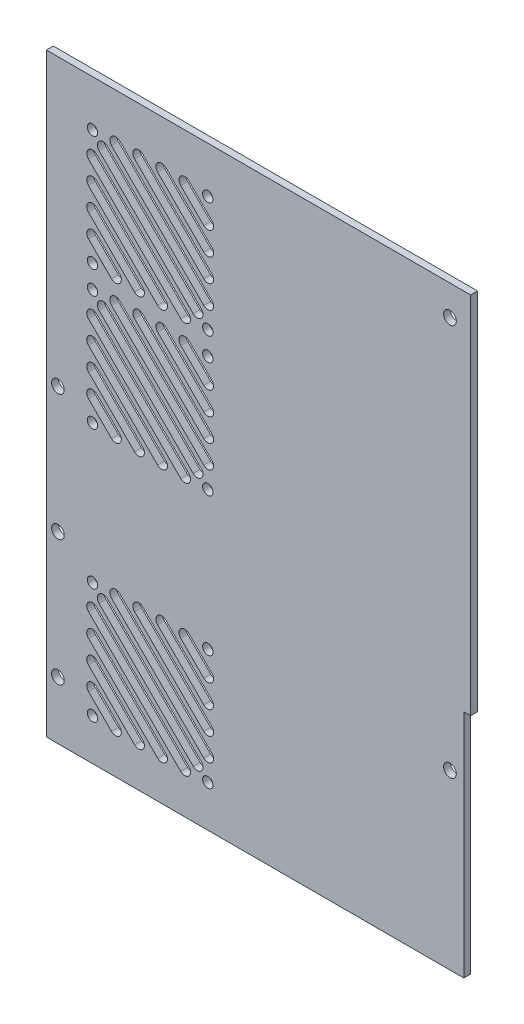
SolidWorks part; units mm, degrees
ref_plane "Front Plane" through (0, 0, 0) normal (0, 0, 1) x (1, 0, 0)
ref_plane "Top Plane" through (0, 0, 0) normal (0, 1, 0) x (1, 0, 0)
ref_plane "Right Plane" through (0, 0, 0) normal (1, 0, 0) x (0, 0, -1)
sketch "Sketch1" plane through (0, 0, 0) normal (0, 0, 1) x (1, 0, 0)
  line L1 (0, 0) -> (184, 0)
  line L2 (0, 0) -> (0, 258)
  line L3 (0, 258) -> (184, 258)
  line L4 (184, 0) -> (184, 258)
  dimension "D1" = 184
  dimension "D2" = 258
extrude "Boss-Extrude1" add sketch "Sketch1" along normal blind 3
sketch "Sketch2" plane through (0, 0, 0) normal (0, 0, -1) x (-1, 0, 0)
  line L0 (-175, 75) -> (-175, 245)
  circle A0 centre (-175, 75) radius 1.7 construction
  circle A1 centre (-5, 134.225) radius 2.2 construction
  circle A2 centre (-5, 79.6125) radius 2.2 construction
  circle A3 centre (-175, 75) radius 1.7
  circle A4 centre (-5, 134.225) radius 2.2
  circle A5 centre (-5, 79.6125) radius 2.2
  circle A6 centre (-5, 25) radius 2.15 construction
  circle A7 centre (-5, 25) radius 2.15
  point P0 (-175, 75)
  point P2 (-5, 134.225)
  point P4 (-5, 79.6125)
  point P11 (-175, 245)
  point P19 (-5, 25)
  dimension "D1" = 170
hole_wizard "M5 Clearance Hole1" positions "Sketch2" profile "Sketch3" hole size "M5" standard "ANSI Metric" end condition through all
sketch "Sketch3" plane through (175, 75, 0) normal (1, 0, 0) x (0, 1, 0)
  line L0 (0, 0) -> (0, 3)
  line L1 (0, 3) -> (2.75, 3)
  line L2 (2.75, 3) -> (2.75, 0)
  line L5 (2.75, 0) -> (0, 0)
  line L11 (0, -6.35) -> (0, 107.95) construction
  dimension "Thru Hole Dia." = 5.5
  dimension "Thru Hole Depth" = 3
sketch "Sketch4" plane through (0, 0, 0) normal (0, 0, -1) x (-1, 0, 0)
  line L1 (-70, 238) -> (-20, 238) construction
  line L2 (-70, 238) -> (-70, 188) construction
  line L3 (-70, 188) -> (-20, 188) construction
  line L4 (-20, 238) -> (-20, 188) construction
  line L5 (0, 258) -> (0, 0) construction
  line L6 (-184, 258) -> (0, 258) construction
  line L7 (-60, 238) -> (-70, 228) construction
  line L8 (-50, 238) -> (-70, 218) construction
  line L9 (-40, 238) -> (-70, 208) construction
  line L10 (-30, 238) -> (-70, 198) construction
  line L11 (-20, 238) -> (-70, 188) construction
  line L12 (-20, 228) -> (-60, 188) construction
  line L13 (-20, 218) -> (-50, 188) construction
  line L14 (-20, 208) -> (-40, 188) construction
  line L15 (-20, 198) -> (-30, 188) construction
  line L16 (-60, 238) -> (-70, 228) construction
  line L17 (-58.2322, 236.2322) -> (-68.2322, 226.2322)
  line L18 (-61.7678, 239.7678) -> (-71.7678, 229.7678)
  line L19 (-50, 238) -> (-70, 218) construction
  line L20 (-48.2322, 236.2322) -> (-68.2322, 216.2322)
  line L21 (-51.7678, 239.7678) -> (-71.7678, 219.7678)
  line L22 (-40, 238) -> (-70, 208) construction
  line L23 (-38.2322, 236.2322) -> (-68.2322, 206.2322)
  line L24 (-41.7678, 239.7678) -> (-71.7678, 209.7678)
  line L25 (-30, 238) -> (-70, 198) construction
  line L26 (-28.2322, 236.2322) -> (-68.2322, 196.2322)
  line L27 (-31.7678, 239.7678) -> (-71.7678, 199.7678)
  line L28 (-65.4038, 192.5962) -> (-24.5962, 233.4038) construction
  line L29 (-67.1716, 194.364) -> (-26.364, 235.1716)
  line L30 (-63.636, 190.8284) -> (-22.8284, 231.636)
  line L31 (-20, 228) -> (-60, 188) construction
  line L32 (-18.2322, 226.2322) -> (-58.2322, 186.2322)
  line L33 (-21.7678, 229.7678) -> (-61.7678, 189.7678)
  line L34 (-50, 188) -> (-20, 218) construction
  line L35 (-51.7678, 189.7678) -> (-21.7678, 219.7678)
  line L36 (-48.2322, 186.2322) -> (-18.2322, 216.2322)
  line L37 (-20, 208) -> (-40, 188) construction
  line L38 (-18.2322, 206.2322) -> (-38.2322, 186.2322)
  line L39 (-21.7678, 209.7678) -> (-41.7678, 189.7678)
  line L40 (-20, 198) -> (-30, 188) construction
  line L41 (-18.2322, 196.2322) -> (-28.2322, 186.2322)
  line L42 (-21.7678, 199.7678) -> (-31.7678, 189.7678)
  circle A0 centre (-70, 238) radius 4
  circle A1 centre (-20, 238) radius 4
  circle A2 centre (-70, 188) radius 4
  circle A3 centre (-20, 188) radius 3
  arc A4 (-58.2322, 236.2322) -> (-61.7678, 239.7678) centre (-60, 238) ccw
  arc A5 (-71.7678, 229.7678) -> (-68.2322, 226.2322) centre (-70, 228) ccw
  arc A6 (-48.2322, 236.2322) -> (-51.7678, 239.7678) centre (-50, 238) ccw
  arc A7 (-71.7678, 219.7678) -> (-68.2322, 216.2322) centre (-70, 218) ccw
  arc A8 (-38.2322, 236.2322) -> (-41.7678, 239.7678) centre (-40, 238) ccw
  arc A9 (-71.7678, 209.7678) -> (-68.2322, 206.2322) centre (-70, 208) ccw
  arc A10 (-28.2322, 236.2322) -> (-31.7678, 239.7678) centre (-30, 238) ccw
  arc A11 (-71.7678, 199.7678) -> (-68.2322, 196.2322) centre (-70, 198) ccw
  arc A12 (-67.1716, 194.364) -> (-63.636, 190.8284) centre (-65.4038, 192.5962) ccw
  arc A13 (-22.8284, 231.636) -> (-26.364, 235.1716) centre (-24.5962, 233.4038) ccw
  arc A14 (-18.2322, 226.2322) -> (-21.7678, 229.7678) centre (-20, 228) ccw
  arc A15 (-61.7678, 189.7678) -> (-58.2322, 186.2322) centre (-60, 188) ccw
  arc A16 (-51.7678, 189.7678) -> (-48.2322, 186.2322) centre (-50, 188) ccw
  arc A17 (-18.2322, 216.2322) -> (-21.7678, 219.7678) centre (-20, 218) ccw
  arc A18 (-18.2322, 206.2322) -> (-21.7678, 209.7678) centre (-20, 208) ccw
  arc A19 (-41.7678, 189.7678) -> (-38.2322, 186.2322) centre (-40, 188) ccw
  arc A20 (-18.2322, 196.2322) -> (-21.7678, 199.7678) centre (-20, 198) ccw
  arc A21 (-31.7678, 189.7678) -> (-28.2322, 186.2322) centre (-30, 188) ccw
  point P28 (-65, 233)
  point P33 (-60, 228)
  point P38 (-55, 223)
  point P43 (-50, 218)
  point P50 (-45, 213)
  point P55 (-40, 208)
  point P60 (-35, 203)
  point P65 (-30, 198)
  point P70 (-25, 193)
  dimension "D14" = 8
  dimension "D15" = 8
  dimension "D16" = 8
  dimension "D17" = 6
  dimension "D18" = 2.5
  dimension "D19" = 2.5
  dimension "D20" = 2.5
  dimension "D21" = 2.5
  dimension "D22" = 2.5
  dimension "D23" = 2.5
  dimension "D24" = 2.5
  dimension "D25" = 2.5
  dimension "D26" = 2.5
  dimension "D1" = 50
  dimension "D2" = 50
  dimension "D3" = 20
  dimension "D4" = 20
  dimension "D5" = 45
  dimension "D6" = 10
  dimension "D7" = 10
  dimension "D8" = 10
  dimension "D9" = 10
  dimension "D10" = 10
  dimension "D11" = 10
  dimension "D12" = 10
  dimension "D13" = 10
extrude "Cut-Extrude1" cut sketch "Sketch4" against normal blind 10 contours L18 A5 L17 A4 | L21 A7 L20 A6 | L24 A9 L23 A8 | L27 A11 L26 A10 | A13 L29 A12 L30 | L33 A15 L32 A14 | L36 A17 L35 A16 | L39 A19 L38 A18 | L42 A21 L41 A20
sketch "Sketch5" plane through (0, 0, 0) normal (0, 0, -1) x (-1, 0, 0)
  point P0 (-20, 188)
  point P2 (-70, 188)
  point P4 (-70, 238)
  point P6 (-20, 238)
hole_wizard "M4 Clearance Hole1" positions "Sketch5" profile "Sketch6" hole size "M4" standard "ANSI Metric" end condition through all
sketch "Sketch6" plane through (20, 188, 0) normal (1, 0, 0) x (0, 1, 0)
  line L0 (0, 0) -> (0, 3)
  line L1 (0, 3) -> (2.25, 3)
  line L2 (2.25, 3) -> (2.25, 0)
  line L5 (2.25, 0) -> (0, 0)
  line L11 (0, -6.35) -> (0, 107.95) construction
  dimension "Thru Hole Dia." = 4.5
  dimension "Thru Hole Depth" = 3
pattern_linear "LPattern1" count 2 spacing 60 along (0, -1, 0) of "Cut-Extrude1", "M4 Clearance Hole1"
pattern_linear "LPattern2" count 2 spacing 170 along (0, -1, 0) of "M4 Clearance Hole1", "Cut-Extrude1"
sketch "Sketch7" plane through (0, 0, 0) normal (0, 0, -1) x (-1, 0, 0)
  line L0 (0, 0) -> (-184, 0) construction
  line L1 (-184, 0) -> (-181, 0)
  line L2 (-184, 0) -> (-184, 100)
  line L3 (-184, 100) -> (-181, 100)
  line L4 (-181, 0) -> (-181, 100)
  line L5 (-184, 0) -> (-184, 258) construction
  point P6 (-184, 0)
  dimension "D1" = 3
  dimension "D2" = 100
extrude "Cut-Extrude2" cut sketch "Sketch7" against normal blind 10
